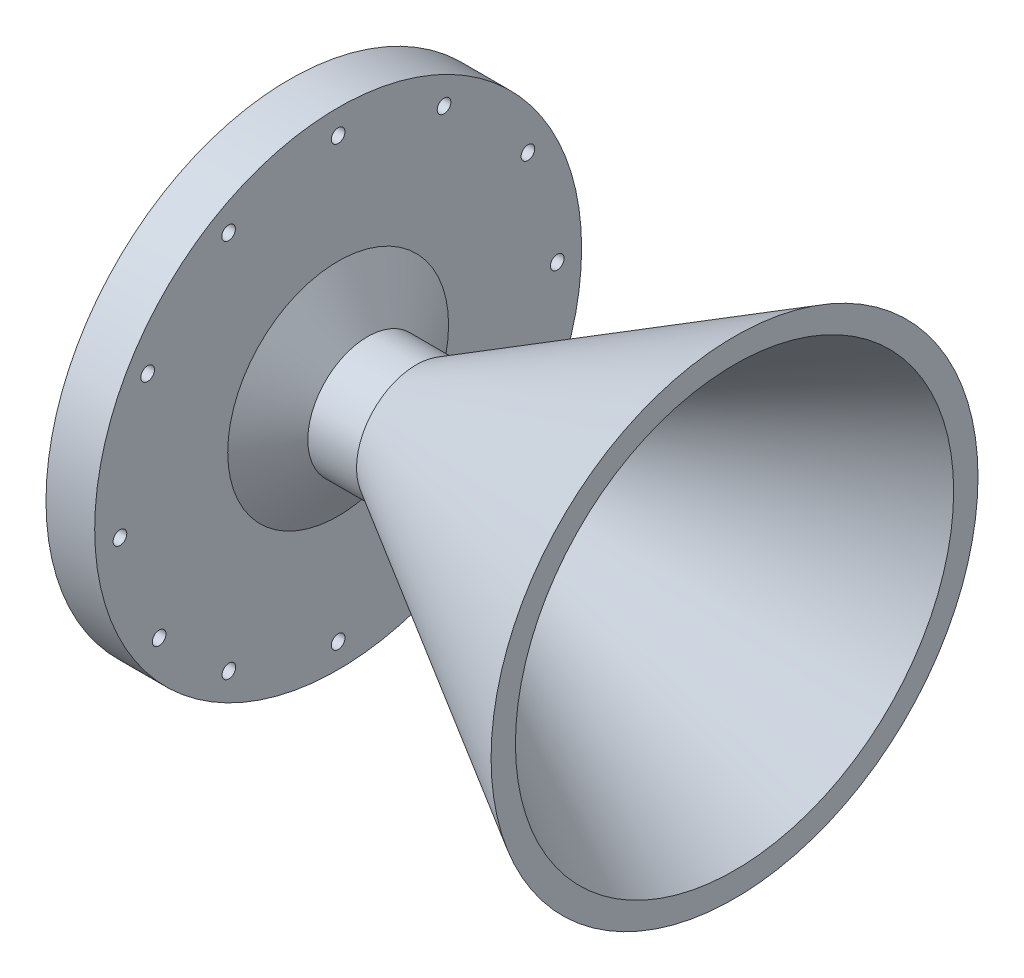
SolidWorks part; units mm, degrees
material "C (Graphite)"
ref_plane "Front Plane" through (0, 0, 0) normal (0, 0, 1) x (1, 0, 0)
ref_plane "Top Plane" through (0, 0, 0) normal (0, 1, 0) x (1, 0, 0)
ref_plane "Right Plane" through (0, 0, 0) normal (1, 0, 0) x (0, 0, -1)
sketch "Sketch1" plane through (0, 0, 0) normal (0, 0, 1) x (1, 0, 0)
  line L0 (0, 0) -> (215.3765, 0) construction
  line L1 (0, 0) -> (0, 93.6004) construction
  line L2 (0, 15.5575) -> (83.0388, 63.5)
  line L3 (0, 7.9375) -> (83.0388, 57.15)
  line L4 (83.0388, 63.5) -> (83.0388, 57.15)
  line L9 (0, 15.5575) -> (-12.7, 15.5575)
  line L10 (0, 7.9375) -> (-12.7, 7.9375)
  line L14 (-12.7, 15.5575) -> (-20.3473, 28.803)
  line L22 (-12.7, 7.9375) -> (-33.0473, 44.45)
  line L23 (-33.0473, 50.8) -> (-33.0473, 44.45)
  line L24 (-33.0473, 50.8) -> (-33.0473, 63.5)
  line L25 (-33.0473, 63.5) -> (-20.3473, 63.5)
  line L26 (-20.3473, 63.5) -> (-20.3473, 28.803)
  dimension "D1" = 6.35
  dimension "D2" = 7.62
  dimension "D3" = 7.9375
  dimension "D4" = 6.35
  dimension "D5" = 12.7
  dimension "D6" = 63.5
  dimension "D7" = 12.7
  dimension "D8" = 30
  dimension "D9" = 60
  dimension "D10" = 50.8
  dimension "D11" = 12.7
  dimension "D12" = 12.7
revolve "Revolve1" add sketch "Sketch1" angle 360 about L0
sketch "Sketch3" plane through (-33.0473, 0, 0) normal (-1, 0, 0) x (0, 0, 1)
  circle A0 centre (56.9124, -5.2056) radius 1.778
  circle A1 centre (0, 57.15) radius 1.778
  circle A2 centre (-57.15, 0) radius 1.778
  circle A3 centre (-27.6158, 50.0349) radius 1.778
  circle A4 centre (-49.4934, 28.575) radius 1.778
  circle A5 centre (28.575, 49.4934) radius 1.778
  circle A6 centre (49.6828, 28.2442) radius 1.778
  circle A7 centre (-30.522, -48.317) radius 1.778
  circle A8 centre (-50.0349, -27.6158) radius 1.778
  circle A9 centre (46.6848, -32.9644) radius 1.778
  circle A10 centre (28.4997, -49.5368) radius 1.778
  circle A11 centre (0, -57.15) radius 1.778
  point P25 (0, 0)
  point P26 (0, 0)
  point P27 (0, 0)
  dimension "D13" = 3.556
  dimension "D14" = 3.556
  dimension "D15" = 3.556
  dimension "D16" = 3.556
  dimension "D17" = 3.556
  dimension "D18" = 3.556
  dimension "D19" = 3.556
  dimension "D20" = 3.556
  dimension "D21" = 3.556
  dimension "D22" = 3.556
  dimension "D23" = 3.556
  dimension "D24" = 3.556
  dimension "D1" = 57.15
  dimension "D2" = 57.15
  dimension "D3" = 57.15
  dimension "D4" = 57.15
  dimension "D5" = 57.15
  dimension "D6" = 57.15
  dimension "D7" = 57.15
  dimension "D8" = 57.15
  dimension "D9" = 57.15
  dimension "D10" = 57.15
  dimension "D11" = 57.15
  dimension "D12" = 57.15
  dimension "D25" = 120
  dimension "D26" = 90
  dimension "D27" = 150
  dimension "D28" = 150
  dimension "D29" = 28.448
extrude "Cut-Extrude1" cut sketch "Sketch3" against normal blind 12.7
